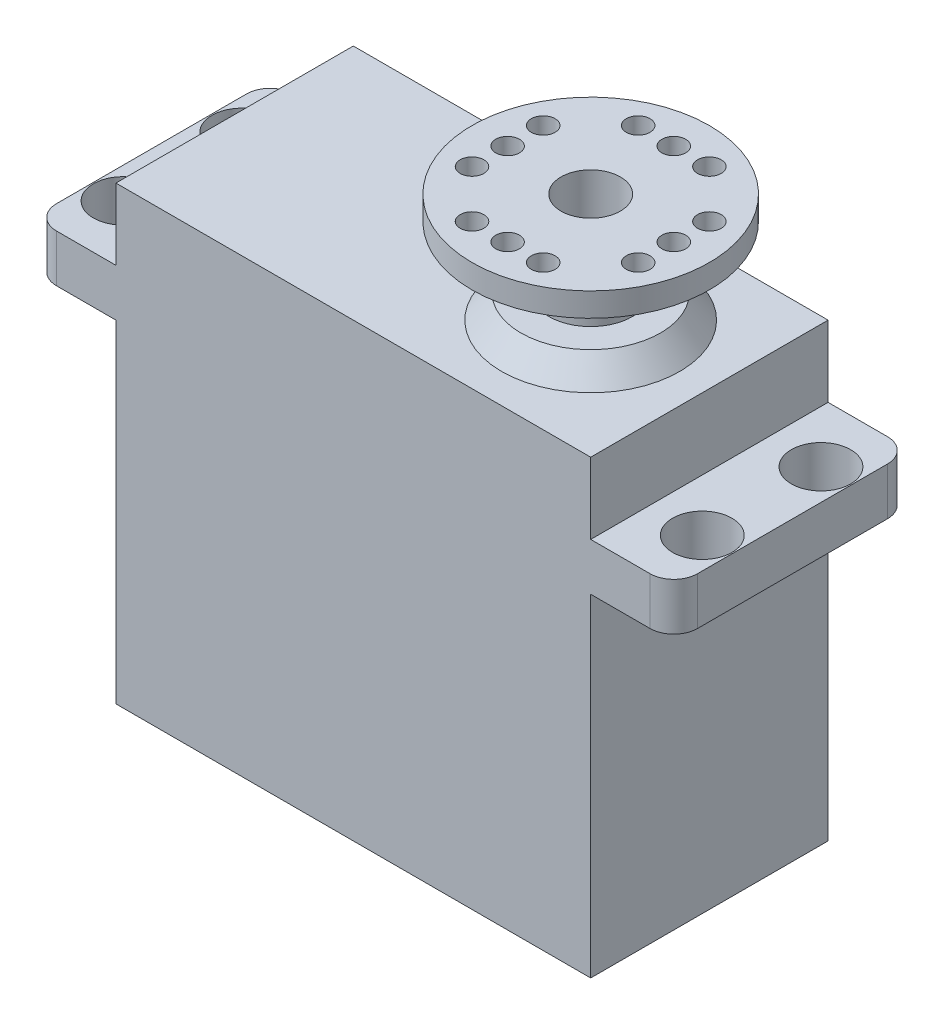
SolidWorks part; units mm, degrees
ref_plane "Front Plane" through (0, 0, 0) normal (0, 0, 1) x (1, 0, 0)
ref_plane "Top Plane" through (0, 0, 0) normal (0, 1, 0) x (1, 0, 0)
ref_plane "Right Plane" through (0, 0, 0) normal (1, 0, 0) x (0, 0, -1)
sketch "Sketch1" plane through (0, 0, 0) normal (0, 1, 0) x (1, 0, 0)
  line L1 (-20, 10) -> (20, 10)
  line L2 (-20, 10) -> (-20, -10)
  line L3 (-20, -10) -> (20, -10)
  line L4 (20, 10) -> (20, -10)
  line L5 (-20, 10) -> (20, -10) construction
  line L6 (-20, -10) -> (20, 10) construction
  point P0 (0, 0)
  dimension "D1" = 20
  dimension "D2" = 40
extrude "Boss-Extrude1" add sketch "Sketch1" along normal blind 38
sketch "Sketch2" plane through (0, 0, 0) normal (1, 0, 0) x (0, 0, -1)
  line L0 (10, 38) -> (10, 0) construction
  line L1 (-10, 32) -> (10, 32)
  line L2 (-10, 32) -> (-10, 28)
  line L3 (-10, 28) -> (10, 28)
  line L4 (10, 32) -> (10, 28)
  line L5 (-10, 32) -> (10, 28) construction
  line L6 (-10, 28) -> (10, 32) construction
  line L7 (-10, 0) -> (10, 0) construction
  point P0 (0, 30)
  dimension "D1" = 4
  dimension "D2" = 28
extrude "Boss-Extrude2" add sketch "Sketch2" along normal mid plane 54
sketch "Sketch3" plane through (0, 32, 0) normal (0, 1, 0) x (1, 0, 0)
  line L0 (27, 10) -> (27, -10) construction
  circle A0 centre (24.4, 5) radius 2.5
  circle A1 centre (24.4, -5) radius 2.5
  dimension "D1" = 5
  dimension "D2" = 2.6
  dimension "D3" = 10
  dimension "D4" = 5
extrude "Cut-Extrude5" cut sketch "Sketch3" against normal blind 53.6
mirror "Mirror1" about plane through (0, 0, 0) normal (1, 0, 0) of "Cut-Extrude5"
sketch "Sketch4" plane through (0, 38, 0) normal (0, 1, 0) x (1, 0, 0)
  circle A0 centre (10, 0) radius 7.5
  dimension "D1" = 15
  dimension "D2" = 10
extrude "Boss-Extrude3" add sketch "Sketch4" along normal blind 2 draft 39
sketch "Sketch5" plane through (0, 40, 0) normal (0, 1, 0) x (1, 0, 0)
  circle A0 centre (10, 0) radius 3.5
  dimension "D1" = 7
extrude "Boss-Extrude4" add sketch "Sketch5" along normal blind 5.2
sketch "Sketch6" plane through (0, 45.2, 0) normal (0, 1, 0) x (1, 0, 0)
  circle A0 centre (10, 0) radius 10
  dimension "D1" = 20
extrude "Boss-Extrude5" add sketch "Sketch6" along normal blind 2
fillet "Fillet1" radius 2 4 edges at (-27, 30, -10) (-27, 30, 10) (27, 30, -10) (27, 30, 10)
sketch "Sketch7" plane through (0, 47.2, 0) normal (0, 1, 0) x (1, 0, 0)
  circle A0 centre (10, 0) radius 2.5
  circle A1 centre (10, 7) radius 1
  circle A2 centre (13, 7) radius 1
  circle A3 centre (7, 7) radius 1
  circle A4 centre (17, 3) radius 1
  circle A5 centre (17, 0) radius 1
  circle A6 centre (17, -3) radius 1
  circle A7 centre (13, -7) radius 1
  circle A8 centre (10, -7) radius 1
  circle A9 centre (7, -7) radius 1
  circle A10 centre (3, -3) radius 1
  circle A11 centre (3, 0) radius 1
  circle A12 centre (3, 3) radius 1
  point P30 (10, 0)
  dimension "D1" = 10
  dimension "D2" = 2
  dimension "D3" = 7
  dimension "D5" = 3
  dimension "D6" = 3
  dimension "D4" = 4
extrude "Cut-Extrude9" cut sketch "Sketch7" against normal blind 6
